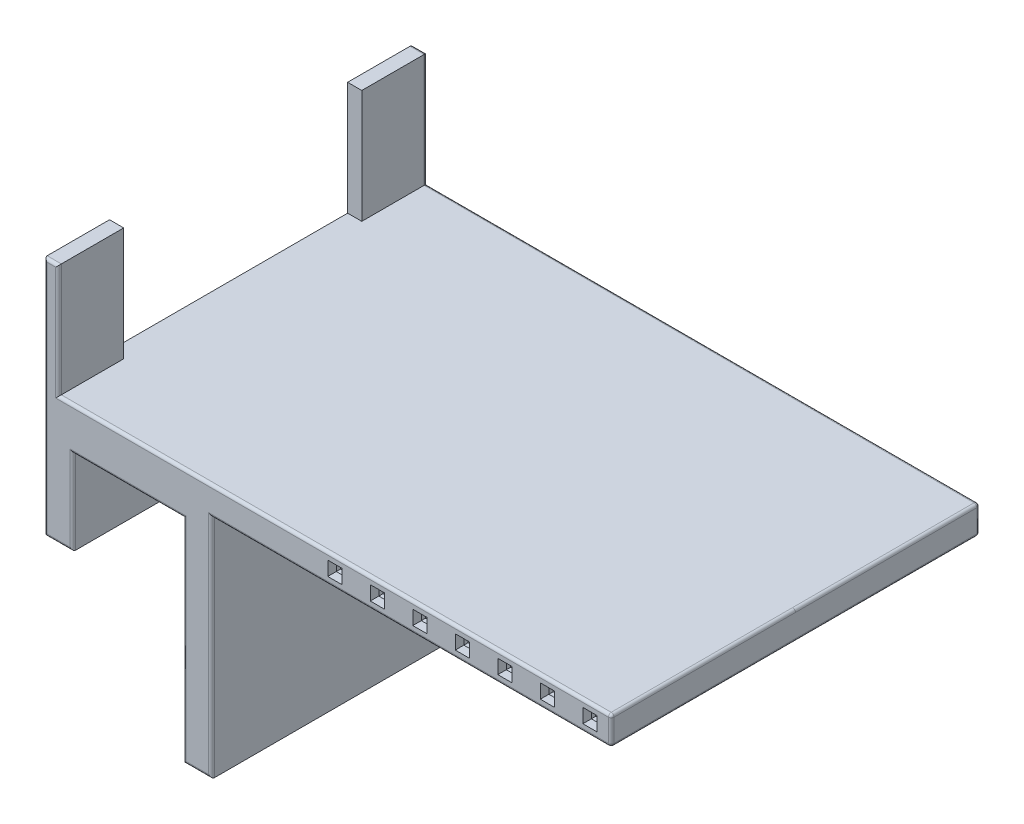
SolidWorks part; units mm, degrees
ref_plane "前视基准面" through (0, 0, 0) normal (0, 0, 1) x (1, 0, 0)
ref_plane "上视基准面" through (0, 0, 0) normal (0, 1, 0) x (1, 0, 0)
ref_plane "右视基准面" through (0, 0, 0) normal (1, 0, 0) x (0, 0, -1)
other "Configuration Table"
sketch "草图1" plane through (0, 0, 0) normal (0, 0, 1) x (1, 0, 0)
  line L3 (190, 35) -> (190, 45)
  line L5 (-10, 45) -> (-10, 0)
  line L20 (-10, 0) -> (0, 0)
  line L21 (190, 45) -> (-10, 45)
  line L22 (190, 35) -> (49, 35)
  line L23 (49, 35) -> (49, -45)
  line L24 (49, -45) -> (39, -45)
  line L29 (39, -45) -> (39, 30)
  line L30 (39, 30) -> (0, 30)
  line L31 (0, 30) -> (0, 0)
  dimension "D1" = 10
  dimension "D2" = 39
  dimension "D3" = 10
  dimension "D4" = 15
  dimension "D5" = 45
  dimension "D7" = 10
  dimension "65" = 80
  dimension "D8" = 200
extrude "凸台-拉伸1" add sketch "草图1" along normal blind 65 contours L5 L20 L31 L30 L29 L24 L23 L22 L3 L21
sketch "草图5" plane through (0, 0, 65) normal (0, 0, 1) x (1, 0, 0)
  line L0 (170, 42.5) -> (170, 37.5)
  line L1 (190, 45) -> (-10, 45) construction
  line L2 (190, 45) -> (-10, 45) construction
  line L3 (190, 35) -> (49, 35) construction
  line L4 (190, 35) -> (49, 35) construction
  line L5 (190, 35) -> (190, 45) construction
  line L6 (190, 35) -> (190, 45) construction
  line L7 (138.6035, 40) -> (51.8163, 40) construction
  line L8 (170, 42.5) -> (165, 42.5)
  line L9 (185, 42.5) -> (180, 42.5)
  line L10 (185, 42.5) -> (185, 37.5)
  line L11 (185, 37.5) -> (180, 37.5)
  line L12 (180, 42.5) -> (180, 37.5)
  line L13 (185, 42.5) -> (180, 37.5) construction
  line L14 (185, 37.5) -> (180, 42.5) construction
  line L15 (165, 42.5) -> (165, 37.5)
  line L16 (170, 37.5) -> (165, 37.5)
  line L17 (155, 42.5) -> (155, 37.5)
  line L18 (155, 42.5) -> (150, 42.5)
  line L19 (150, 42.5) -> (150, 37.5)
  line L20 (155, 37.5) -> (150, 37.5)
  line L21 (140, 42.5) -> (140, 37.5)
  line L22 (140, 42.5) -> (135, 42.5)
  line L23 (135, 42.5) -> (135, 37.5)
  line L24 (140, 37.5) -> (135, 37.5)
  line L25 (125, 42.5) -> (125, 37.5)
  line L26 (125, 42.5) -> (120, 42.5)
  line L27 (120, 42.5) -> (120, 37.5)
  line L28 (125, 37.5) -> (120, 37.5)
  line L29 (110, 42.5) -> (110, 37.5)
  line L30 (110, 42.5) -> (105, 42.5)
  line L31 (105, 42.5) -> (105, 37.5)
  line L32 (110, 37.5) -> (105, 37.5)
  line L33 (95, 42.5) -> (95, 37.5)
  line L34 (95, 42.5) -> (90, 42.5)
  line L35 (90, 42.5) -> (90, 37.5)
  line L36 (95, 37.5) -> (90, 37.5)
  point P6 (182.5, 40)
  point P13 (190, 40)
  dimension "D1" = 5
  dimension "D2" = 5
  dimension "D3" = 7
extrude "切除-拉伸1" cut sketch "草图5" along direction (0, 0, 1) on the side against the normal blind 3
sketch "草图7" plane through (0, 45, 0) normal (0, 1, 0) x (1, 0, 0)
  line L0 (-10, -65) -> (-10, 0) construction
  line L1 (-10, -65) -> (-10, 55) construction
  line L2 (-10, -65) -> (-10, -42)
  line L3 (-10, -42) -> (-5, -42)
  line L4 (-5, -42) -> (-5, -65)
  line L5 (190, -65) -> (-10, -65) construction
  line L6 (-5, -65) -> (-10, -65)
  dimension "D1" = 23
  dimension "D2" = 5
extrude "凸台-拉伸2" add sketch "草图7" along normal blind 40
fillet "圆角1" radius 1 14 edges at (190, 40, 65) (119.5, 35, 65) (49, -5, 65) (44, -45, 65) (39, -7.5, 65) (19.5, 30, 65) (0, 15, 65) (-5, 0, 65) (-10, 42.5, 65) (-7.5, 85, 65) (-5, 65, 65) (92.5, 45, 65) (190, 35, 32.5) (190, 45, 32.5)
sketch "草图8" plane through (0, 0, 62) normal (0, 0, 1) x (1, 0, 0)
  line L0 (179.5, 43) -> (179.5, 37)
  line L1 (179.5, 37) -> (185.5, 37)
  line L2 (185.5, 37) -> (185.5, 43)
  line L3 (185.5, 43) -> (179.5, 43)
  line L4 (180, 42.5) -> (180, 37.5)
  line L5 (180, 37.5) -> (185, 37.5)
  line L6 (185, 37.5) -> (185, 42.5)
  line L7 (185, 42.5) -> (180, 42.5)
  line L8 (180, 42.5) -> (180, 37.5) construction
  line L9 (180, 37.5) -> (185, 37.5) construction
  line L10 (185, 37.5) -> (185, 42.5) construction
  line L11 (185, 42.5) -> (180, 42.5) construction
  line L12 (170.5, 43) -> (164.5, 43)
  line L13 (164.5, 43) -> (164.5, 37)
  line L14 (164.5, 37) -> (170.5, 37)
  line L15 (170.5, 37) -> (170.5, 43)
  line L16 (155.5, 43) -> (149.5, 43)
  line L17 (149.5, 43) -> (149.5, 37)
  line L18 (149.5, 37) -> (155.5, 37)
  line L19 (155.5, 37) -> (155.5, 43)
  line L20 (140.5, 43) -> (134.5, 43)
  line L21 (134.5, 43) -> (134.5, 37)
  line L22 (134.5, 37) -> (140.5, 37)
  line L23 (140.5, 37) -> (140.5, 43)
  line L24 (125.5, 43) -> (119.5, 43)
  line L25 (119.5, 43) -> (119.5, 37)
  line L26 (119.5, 37) -> (125.5, 37)
  line L27 (125.5, 37) -> (125.5, 43)
  line L28 (110.5, 43) -> (104.5, 43)
  line L29 (104.5, 43) -> (104.5, 37)
  line L30 (104.5, 37) -> (110.5, 37)
  line L31 (110.5, 37) -> (110.5, 43)
  line L32 (95.5, 43) -> (89.5, 43)
  line L33 (89.5, 43) -> (89.5, 37)
  line L34 (89.5, 37) -> (95.5, 37)
  line L35 (95.5, 37) -> (95.5, 43)
  dimension "D1" = 0
  dimension "D2" = 0.5
  dimension "D3" = 7
extrude "切除-拉伸2" cut sketch "草图8" against normal blind 2
mirror "镜向3" about plane through (0, 0, 0) normal (0, 0, 1) of "圆角1", "凸台-拉伸1", "切除-拉伸1", "凸台-拉伸2"
